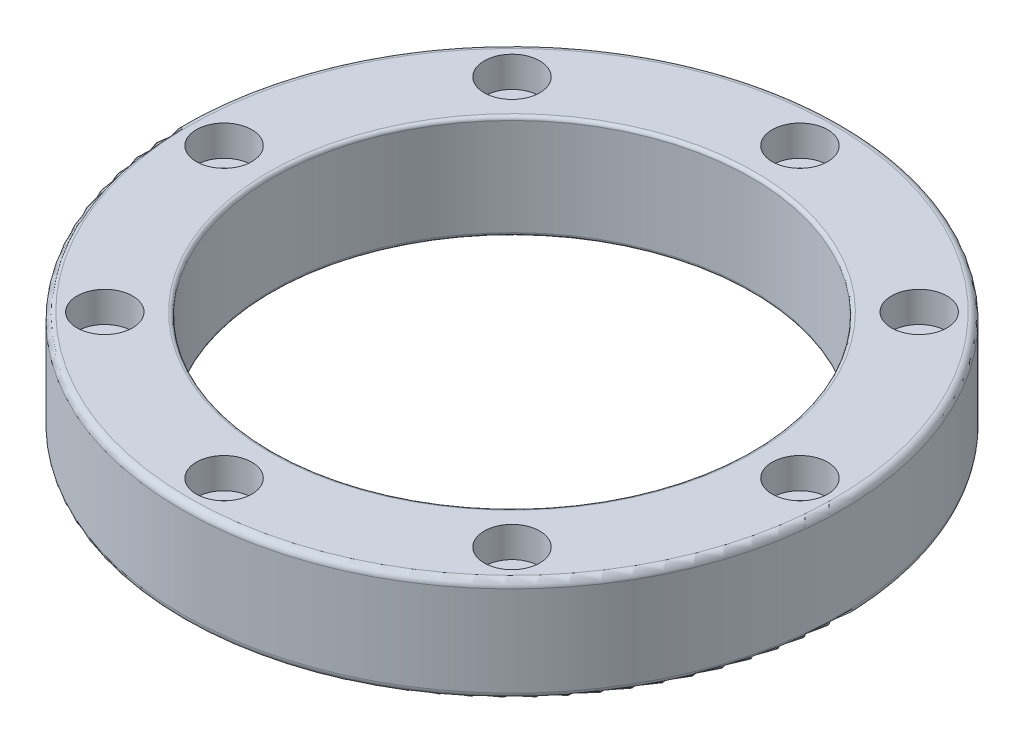
SolidWorks part; units mm, degrees
ref_plane "Front Plane" through (0, 0, 0) normal (0, 0, 1) x (1, 0, 0)
ref_plane "Top Plane" through (0, 0, 0) normal (0, 1, 0) x (1, 0, 0)
ref_plane "Right Plane" through (0, 0, 0) normal (1, 0, 0) x (0, 0, -1)
sketch "Sketch1" plane through (0, 0, 0) normal (0, 1, 0) x (1, 0, 0)
  circle A0 centre (0, 0) radius 34.5
  circle A1 centre (0, 0) radius 47.5
  dimension "D1" = 69
  dimension "D2" = 95
extrude "Boss-Extrude1" add sketch "Sketch1" along normal blind 15
sketch "Sketch2" plane through (0, 15, 0) normal (0, 1, 0) x (1, 0, 0)
  circle A0 centre (0, 0) radius 41.5 construction
  circle A1 centre (0, 41.5) radius 2.25
  circle A2 centre (29.3449, 29.3449) radius 2.25
  circle A3 centre (41.5, 0) radius 2.25
  circle A4 centre (29.3449, -29.3449) radius 2.25
  circle A5 centre (0, -41.5) radius 2.25
  circle A6 centre (-29.3449, -29.3449) radius 2.25
  circle A7 centre (-41.5, 0) radius 2.25
  circle A8 centre (-29.3449, 29.3449) radius 2.25
  point P22 (0, 0)
  dimension "D1" = 83
  dimension "D2" = 4.5
  dimension "D3" = 8
extrude "Cut-Extrude1" cut sketch "Sketch2" against normal through all
sketch "Sketch3" plane through (0, 15, 0) normal (0, 1, 0) x (1, 0, 0)
  circle A32 centre (0, 0) radius 41.5 construction
  circle A33 centre (0, 41.5) radius 4
  circle A34 centre (29.3449, 29.3449) radius 4
  circle A35 centre (41.5, 0) radius 4
  circle A36 centre (29.3449, -29.3449) radius 4
  circle A37 centre (0, -41.5) radius 4
  circle A38 centre (-29.3449, -29.3449) radius 4
  circle A39 centre (-41.5, 0) radius 4
  circle A40 centre (-29.3449, 29.3449) radius 4
  point P20 (0, 0)
  dimension "D1" = 8
  dimension "D2" = 8
extrude "Cut-Extrude2" cut sketch "Sketch3" against normal blind 4.4
fillet "Fillet1" radius 1 2 edges at (0, 0, 47.5) (0, 15, 47.5)
fillet "Fillet2" radius 0.5 2 edges at (0, 0, 34.5) (0, 15, 34.5)
